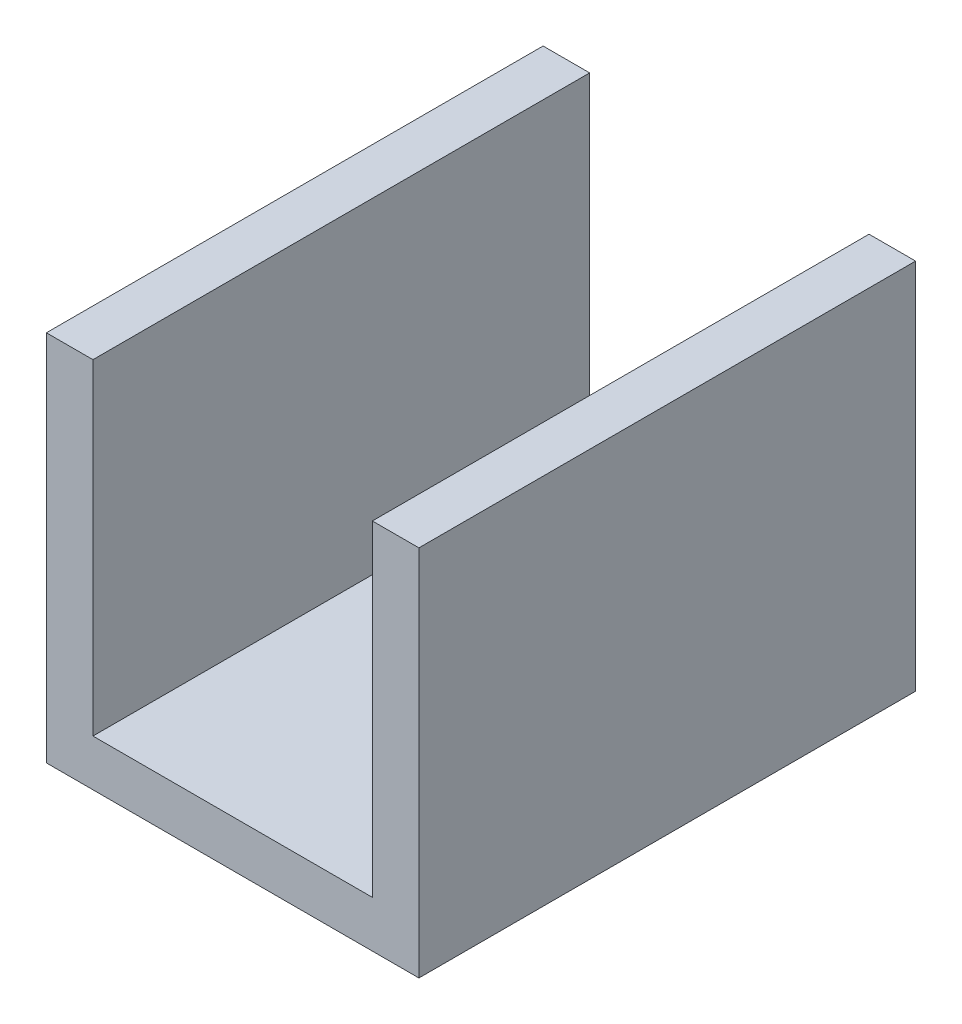
SolidWorks part; units mm, degrees
ref_plane "Front" through (0, 0, 0) normal (0, 0, 1) x (1, 0, 0)
ref_plane "Top" through (0, 0, 0) normal (0, 1, 0) x (1, 0, 0)
ref_plane "Right" through (0, 0, 0) normal (1, 0, 0) x (0, 0, -1)
sketch "Sketch1" plane through (0, 0, 0) normal (0, 0, 1) x (1, 0, 0)
  line L0 (-7.1437, 19.05) -> (-9.525, 19.05)
  line L1 (-9.525, 19.05) -> (-9.525, 0)
  line L2 (-9.525, 0) -> (9.525, 0)
  line L3 (9.525, 0) -> (9.525, 19.05)
  line L4 (9.525, 19.05) -> (7.1437, 19.05)
  line L5 (7.1437, 19.05) -> (7.1438, 2.3812)
  line L6 (7.1438, 2.3812) -> (-7.1438, 2.3812)
  line L7 (-7.1438, 2.3812) -> (-7.1437, 19.05)
  dimension "Leg THickness" = 2.3813
  dimension "BaseThickness" = 2.3813
  dimension "LegLength" = 19.05
  dimension "BaseWidth" = 19.05
extrude "Boss-Extrude1" add sketch "Sketch1" along normal mid plane 25.4
